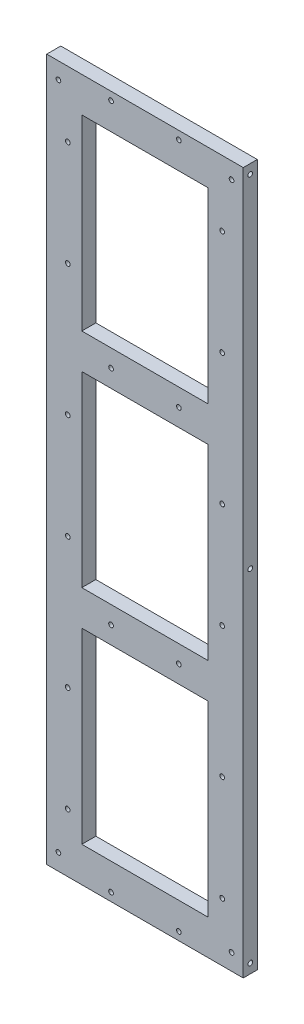
SolidWorks part; units mm, degrees
material "Alumina"
ref_plane "Front Plane" through (0, 0, 0) normal (0, 0, 1) x (1, 0, 0)
ref_plane "Top Plane" through (0, 0, 0) normal (0, 1, 0) x (1, 0, 0)
ref_plane "Right Plane" through (0, 0, 0) normal (1, 0, 0) x (0, 0, -1)
sketch "Sketch1" plane through (0, 0, 0) normal (0, 0, 1) x (1, 0, 0)
  line L0 (27, 135) -> (27, 55)
  line L9 (-42, -150) -> (42, -150)
  line L10 (-42, -150) -> (-42, 150)
  line L11 (-42, 150) -> (42, 150)
  line L12 (42, -150) -> (42, 150)
  line L13 (0, 0) -> (0, 40) construction
  line L15 (-27, -135) -> (27, -135)
  line L16 (-27, -135) -> (-27, -55)
  line L17 (-27, 135) -> (27, 135)
  line L21 (-27, 55) -> (27, 55)
  line L23 (-27, 40) -> (27, 40)
  line L25 (-27, -40) -> (27, -40)
  line L27 (-27, -55) -> (27, -55)
  line L33 (27, 40) -> (27, -40)
  line L34 (-27, 55) -> (-27, 135)
  line L35 (-27, -40) -> (-27, 40)
  line L36 (27, -55) -> (27, -135)
  dimension "D1" = 84
  dimension "D2" = 300
  dimension "D3" = 54
  dimension "D4" = 270
  dimension "D5" = 15
  dimension "D6" = 80
  dimension "D7" = 15
  dimension "D8" = 80
  dimension "D9" = 15
  dimension "D10" = 15
  dimension "D11" = 80
  dimension "D12" = 40
  dimension "D13" = 15
extrude "Boss-Extrude1" add sketch "Sketch1" along normal blind 6
sketch "Sketch2" plane through (42, 0, 0) normal (1, 0, 0) x (0, 0, -1)
  line L0 (-6, 150) -> (0, 150) construction
  line L1 (-6, -150) -> (-6, 150) construction
  line L3 (-3, 146) -> (-3, 0) construction
  circle A0 centre (-3, 146) radius 1
  circle A4 centre (-3, 0) radius 1
  circle A5 centre (-3, -146) radius 1
  circle A6 centre (-3, -292) radius 1
  dimension "D1" = 4
  dimension "D3" = 2
  dimension "D4" = 3
  dimension "D2" = 4
  dimension "D5" = 146
extrude "Cut-Extrude1" cut sketch "Sketch2" against normal blind 10
mirror "Mirror1" about plane through (0, 0, 0) normal (1, 0, 0) of "Cut-Extrude1"
sketch "Sketch4" plane through (0, 0, 6) normal (0, 0, 1) x (1, 0, 0)
  line L0 (-42, -150) -> (-42, 150) construction
  line L2 (-42, 150) -> (42, 150) construction
  line L3 (42, 150) -> (-42, 150) construction
  line L4 (-42, -150) -> (42, -150) construction
  line L5 (-42, 150) -> (-42, -150) construction
  line L6 (27, -55) -> (-27, -55) construction
  line L7 (27, 40) -> (-27, 40) construction
  line L8 (-33, 122) -> (-33, -125) construction
  line L9 (0, -3.3) -> (0, 3.3) construction
  line L10 (33, 122) -> (33, -125) construction
  circle A0 centre (-14.5, 146.5) radius 1
  circle A8 centre (-33, 122) radius 1
  circle A20 centre (-14.5, 47.5) radius 1
  circle A22 centre (-14.5, -47.5) radius 1
  circle A24 centre (-14.5, -146.5) radius 1
  circle A40 centre (-33, -125) radius 1
  circle A41 centre (-33, 77) radius 1
  circle A42 centre (-33, -80) radius 1
  circle A43 centre (-33, 21) radius 1
  circle A44 centre (-33, -24) radius 1
  circle A45 centre (33, -24) radius 1
  circle A46 centre (33, 21) radius 1
  circle A47 centre (33, -80) radius 1
  circle A48 centre (33, 77) radius 1
  circle A49 centre (33, -125) radius 1
  circle A50 centre (14.5, -146.5) radius 1
  circle A51 centre (14.5, -47.5) radius 1
  circle A52 centre (14.5, 47.5) radius 1
  circle A53 centre (33, 122) radius 1
  circle A54 centre (14.5, 146.5) radius 1
  dimension "D1" = 27.5
  dimension "D4" = 27.5
  dimension "D7" = 2
  dimension "D10" = 2
  dimension "D11" = 7.5
  dimension "D3" = 3.5
  dimension "D6" = 25
  dimension "D14" = 2
  dimension "D15" = 27.5
  dimension "D16" = 2
  dimension "D17" = 2
  dimension "D12" = 2
  dimension "D2" = 3.5
  dimension "D8" = 7.5
  dimension "D18" = 2
  dimension "D19" = 45
  dimension "D20" = 2
  dimension "D22" = 2
  dimension "D23" = 2
  dimension "D24" = 45
  dimension "D25" = 56
  dimension "D21" = 56
  dimension "D5" = 28
  dimension "D9" = 9
  dimension "D13" = 27.5
extrude "Cut-Extrude3" cut sketch "Sketch4" against normal blind 10
sketch "Sketch5" plane through (0, 0, 6) normal (0, 0, 1) x (1, 0, 0)
  line L0 (-37, 143) -> (37, 143) construction
  line L1 (37, 143) -> (37, -143) construction
  line L2 (37, -143) -> (-37, -143) construction
  line L3 (-37, -143) -> (-37, 143) construction
  line L4 (-42, 150) -> (-42, -150) construction
  line L5 (42, 150) -> (-42, 150) construction
  line L6 (42, -150) -> (42, 150) construction
  line L7 (-42, -150) -> (42, -150) construction
  circle A0 centre (-37, -143) radius 1
  circle A1 centre (37, -143) radius 1
  circle A2 centre (-37, 143) radius 1
  circle A3 centre (37, 143) radius 1
  dimension "D5" = 2
  dimension "D6" = 2
  dimension "D7" = 2
  dimension "D8" = 2
  dimension "D1" = 5
  dimension "D2" = 7
  dimension "D3" = 5
  dimension "D4" = 7
extrude "Cut-Extrude4" cut sketch "Sketch5" against normal blind 10
